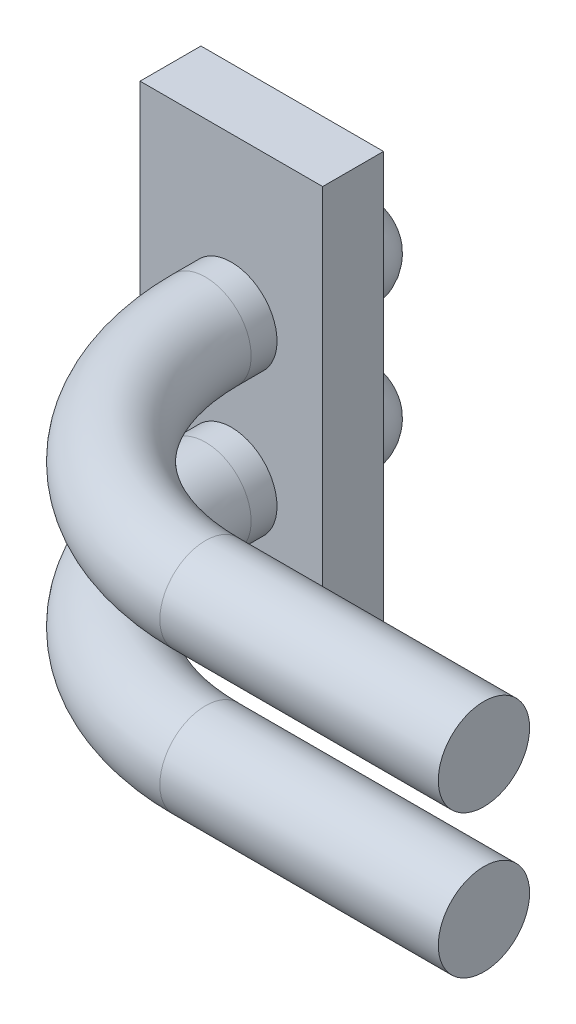
SolidWorks part; units mm, degrees
ref_plane "Front Plane" through (0, 0, 0) normal (0, 0, 1) x (1, 0, 0)
ref_plane "Top Plane" through (0, 0, 0) normal (0, 1, 0) x (1, 0, 0)
ref_plane "Right Plane" through (0, 0, 0) normal (1, 0, 0) x (0, 0, -1)
sketch "Sketch1" plane through (0, 0, 0) normal (0, 0, 1) x (1, 0, 0)
  line L1 (-3, -7.5) -> (3, -7.5)
  line L2 (-3, -7.5) -> (-3, 7.5)
  line L3 (-3, 7.5) -> (3, 7.5)
  line L4 (3, -7.5) -> (3, 7.5)
  line L5 (-3, -7.5) -> (3, 7.5) construction
  line L6 (-3, 7.5) -> (3, -7.5) construction
  point P0 (0, 0)
  dimension "D1" = 15
  dimension "D2" = 6
extrude "Boss-Extrude1" add sketch "Sketch1" along normal blind 2
sketch "Sketch2" plane through (0, 0, 0) normal (0, 0, -1) x (-1, 0, 0)
  circle A0 centre (0, 2.35) radius 1.5
  circle A1 centre (0, -2.35) radius 1.5
  dimension "D2" = 3
  dimension "D1" = 4.7
  dimension "D3" = 2.35
extrude "Boss-Extrude2" add sketch "Sketch2" along normal blind 3
fillet "Fillet1" radius 1.5 2 edges at (-1.5, -2.35, -3) (-1.5, 2.35, -3)
sketch "Sketch3" plane through (0, 0, 2) normal (0, 0, 1) x (1, 0, 0)
  circle A0 centre (0, -2.35) radius 1.5 construction
  circle A1 centre (0, 2.35) radius 1.5 construction
  circle A2 centre (0, -2.35) radius 1.5
  circle A3 centre (0, 2.35) radius 1.5
ref_plane "Plane1" through (0, 2.35, 0) normal (0, 1, 0) x (-1, 0, 0)
sketch "Sketch4" plane through (0, 2.35, 0) normal (0, 1, 0) x (-1, 0, 0)
  line L0 (0, 2) -> (0, 2.85)
  line L1 (1.5, 2) -> (-1.5, 2) construction
  line L2 (-7.5, 10.35) -> (-16.65, 10.35)
  arc A0 (0, 2.85) -> (-7.5, 10.35) centre (-7.5, 2.85) ccw
  point P8 (0, 10.35)
  dimension "D3" = 7.5
  dimension "D1" = 16.65
  dimension "D2" = 8.35
sweep "Sweep1" add profiles "Sketch3" path "Sketch4"
